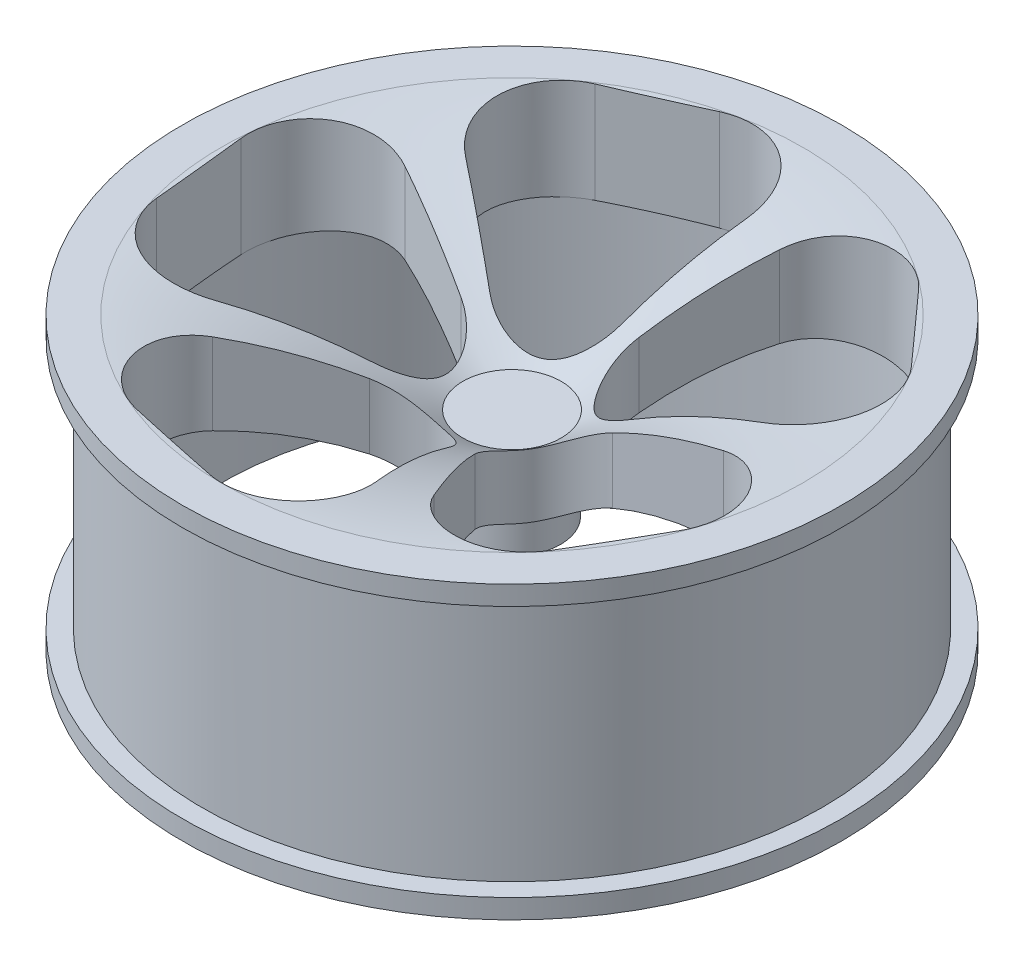
SolidWorks part; units mm, degrees
ref_plane "Front Plane" through (0, 0, 0) normal (0, 0, 1) x (1, 0, 0)
ref_plane "Top Plane" through (0, 0, 0) normal (0, 1, 0) x (1, 0, 0)
ref_plane "Right Plane" through (0, 0, 0) normal (1, 0, 0) x (0, 0, -1)
sketch "Sketch1" plane through (0, 0, 0) normal (0, 1, 0) x (1, 0, 0)
  circle A0 centre (0, 0) radius 50
  dimension "D1" = 100
extrude "Boss-Extrude1" add sketch "Sketch1" along normal blind 30
sketch "Sketch2" plane through (0, 0, 0) normal (0, 0, 1) x (1, 0, 0)
  line L0 (0, -1000) -> (0, 49000) construction
  line L1 (-320, 160) -> (-340, 160)
  line L2 (-340, 160) -> (-340, 180)
  line L3 (-340, 180) -> (-300, 180)
  line L4 (-300, 180) -> (-300, -120)
  line L5 (-300, -120) -> (-340, -120)
  line L6 (-340, -120) -> (-340, -100)
  line L7 (-340, -100) -> (-320, -100)
  line L8 (-320, -100) -> (-320, 160)
  line L9 (50, 30) -> (-50, 30) construction
  dimension "D1" = 300
  dimension "D2" = 20
  dimension "D3" = 20
  dimension "D4" = 300
  dimension "D5" = 150
  dimension "D6" = 40
revolve "Revolve1" add sketch "Sketch2" angle 360 about L0
sketch "Sketch3" plane through (0, 30, 0) normal (0, 1, 0) x (1, 0, 0)
  line L0 (101.6899, 21.4283) -> (214.0556, 45.1063)
  line L1 (251.7243, 160.3499) -> (186.6027, 232.9305)
  line L2 (67.9646, 207.9308) -> (32.2874, 98.7802)
  line L3 (218.7561, -0.384) -> (103.9229, -0.1824)
  line L4 (51.8035, -90.0911) -> (109.0455, -189.6403)
  line L5 (230.2889, -189.8532) -> (279.1935, -105.4902)
  line L6 (67.2342, -208.1681) -> (31.9404, -98.8929)
  line L7 (-69.6736, -77.1077) -> (-146.6618, -162.3105)
  line L8 (-109.3979, -277.6856) -> (-14.0517, -298.1271)
  line L9 (-177.2031, -128.271) -> (-84.1826, -60.9368)
  line L10 (-94.8641, 42.4359) -> (-199.6875, 89.3269)
  line L11 (-297.9005, 18.234) -> (-287.8779, -78.7624)
  line L12 (-176.7517, 128.8923) -> (-83.9682, 61.2319)
  line L13 (11.0443, 103.3345) -> (23.2481, 217.5176)
  line L14 (-74.7147, 288.9548) -> (-163.8667, 249.4492)
  arc A0 (101.6899, 21.4283) -> (32.2874, 98.7802) centre (89.3182, 80.139) cw
  circle A1 centre (0, 0) radius 340
  circle A2 centre (0, 0) radius 340
  arc A3 (251.7243, 160.3499) -> (214.0556, 45.1063) centre (199.622, 113.6021) cw
  arc A4 (186.6027, 232.9305) -> (67.9646, 207.9308) centre (134.5004, 186.1827) ccw
  arc A5 (279.1935, -105.4902) -> (218.7561, -0.384) centre (218.6332, -70.3839) ccw
  arc A6 (51.8035, -90.0911) -> (103.9229, -0.1824) centre (103.8176, -60.1823) cw
  arc A7 (230.2889, -189.8532) -> (109.0455, -189.6403) centre (169.7286, -154.7468) cw
  arc A8 (-14.0517, -298.1271) -> (67.2342, -208.1681) centre (0.6223, -229.6824) ccw
  arc A9 (-69.6736, -77.1077) -> (31.9404, -98.8929) centre (-25.1554, -117.3337) cw
  arc A10 (-109.3979, -277.6856) -> (-146.6618, -162.3105) centre (-94.7239, -209.2409) cw
  arc A11 (-287.8779, -78.7624) -> (-177.2031, -128.271) centre (-218.2486, -71.5676) ccw
  arc A12 (-94.8641, 42.4359) -> (-84.1826, -60.9368) centre (-119.3645, -12.3339) cw
  arc A13 (-297.9005, 18.234) -> (-199.6875, 89.3269) centre (-228.2712, 25.4288) cw
  arc A14 (-163.8667, 249.4492) -> (-176.7517, 128.8923) centre (-135.5074, 185.4511) ccw
  arc A15 (11.0443, 103.3345) -> (-83.9682, 61.2319) centre (-48.6159, 109.711) cw
  arc A16 (-74.7147, 288.9548) -> (23.2481, 217.5176) centre (-46.3555, 224.9568) cw
  point P10 (332.6938, 70.1061)
  point P13 (105.6332, 323.1743)
  point P52 (0, 0)
  dimension "D3" = 60
  dimension "D4" = 70
  dimension "D2" = 60
  dimension "D1" = 0
  dimension "D5" = 5
extrude "Boss-Extrude2" add sketch "Sketch3" along normal through all
sketch "Sketch4" plane through (0, 0, 0) normal (0, 0, 1) x (1, 0, 0)
  line L0 (0, -1000) -> (0, 49000) construction
  line L1 (-300, 244.5245) -> (-300, 50.6937)
  line L2 (-320, 30) -> (320, 30) construction
  line L3 (-50.6995, 95.53) -> (0, 95.53)
  line L4 (0, 95.53) -> (0, 30)
  line L5 (-300, 190.1132) -> (0, 193.8244)
  line L6 (0, 193.8244) -> (0, 95.53)
  line L7 (-50.6995, 30) -> (-300, 30)
  line L8 (-300, 30) -> (-300, 50.6937)
  line L9 (340, 180) -> (-340, 180) construction
  arc A0 (-50.6995, 30) -> (-300, 75.5261) centre (-225.7504, -223.2305) ccw
  arc A1 (-50.6995, 95.53) -> (-300, 180) centre (-329.1694, -316.2106) ccw
  point P17 (-300, 180)
  dimension "D1" = 300
revolve "Cut-Revolve1" cut sketch "Sketch4" angle 360 about L0
sketch "Sketch5" plane through (0, 0, 0) normal (1, 0, 0) x (0, 0, -1)
  line L0 (0, -1000) -> (0, 49000) construction
  line L1 (-320, 30) -> (-320, 160)
  line L2 (-320, 30) -> (320, 30) construction
  line L3 (-320, 30) -> (-320, -100) construction
  line L4 (-320, 160) -> (-340, 160)
  line L5 (-340, 180) -> (-340, 30) construction
  line L6 (-340, 160) -> (-340, 30)
  line L7 (-340, 30) -> (-320, 30)
  line L8 (340, 180) -> (-340, 180) construction
  dimension "D1" = 20
revolve "Cut-Revolve2" cut sketch "Sketch5" angle 360 about L0
